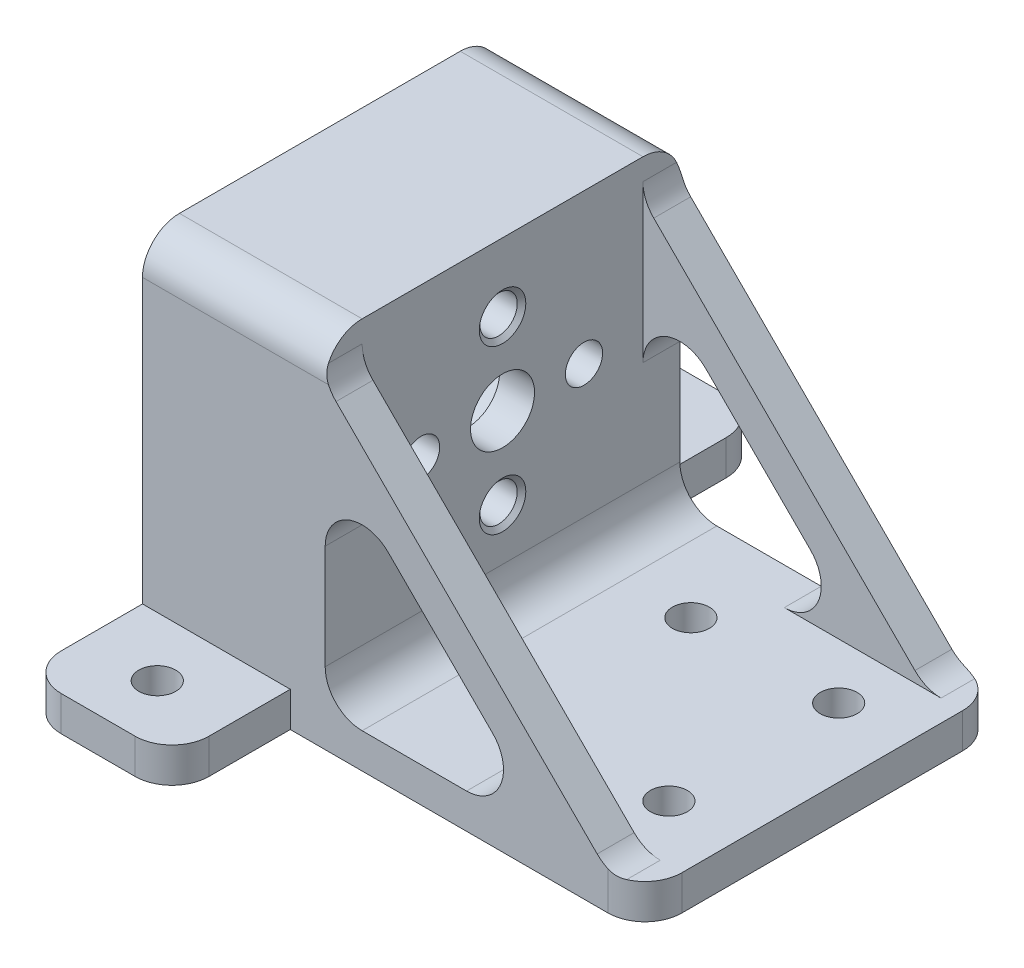
SolidWorks part; units mm, degrees
ref_plane "Front" through (0, 0, 0) normal (0, 0, 1) x (1, 0, 0)
ref_plane "Top" through (0, 0, 0) normal (0, 1, 0) x (1, 0, 0)
ref_plane "Right" through (0, 0, 0) normal (1, 0, 0) x (0, 0, -1)
ref_plane "Plane1" through (0, 0, 0) normal (0, -1, 0) x (1, 0, 0)
sketch "Sketch1" plane through (0, 0, 0) normal (0, -1, 0) x (1, 0, 0)
  line L0 (-15.24, -15.24) -> (15.24, -15.24)
  line L1 (15.24, -15.24) -> (15.24, 15.24)
  line L2 (15.24, 15.24) -> (-15.24, 15.24)
  line L3 (-15.24, 15.24) -> (-15.24, -15.24)
extrude "Boss-Extrude1" add sketch "Sketch1" against normal blind 30.48
sketch "Sketch2" plane through (0, 0, -15.24) normal (0, 0, -1) x (-1, 0, 0)
  line L0 (-15.24, 3) -> (12.24, 3)
  line L1 (12.24, 3) -> (12.24, 30.48)
  line L2 (12.24, 30.48) -> (-15.24, 30.48)
  line L3 (-15.24, 30.48) -> (-15.24, 3)
extrude "Cut-Extrude1" cut sketch "Sketch2" against normal through all
sketch "Sketch4" plane through (0, 3, 0) normal (0, 1, 0) x (-1, 0, 0)
  line L0 (0, 0) -> (-23.6312, 0) construction
  line L1 (12.24, 15.24) -> (12.24, -15.24) construction
  point P3 (-9.35, -7.2958)
  point P4 (-9.35, 7.2958)
  point P5 (3.35, 7.2958)
  point P6 (3.35, -7.2958)
  dimension "D1" = 14.5915
  dimension "D2" = 12.7
  dimension "D3" = 8.89
hole_wizard "#10 Clearance Hole1" positions "Sketch8" profile "Sketch7" hole size "#10" standard "ANSI Inch" end condition through all
sketch "Sketch8" plane through (-12.24, 0, 0) normal (1, 0, 0) x (0, 0, -1)
  line L0 (15.24, 3) -> (15.24, 30.48) construction
  line L1 (-15.24, 30.48) -> (15.24, 30.48) construction
  point P0 (0, 17.605)
  dimension "D1" = 15.24
  dimension "D2" = 12.875
sketch "Sketch7" plane through (-12.24, 17.605, 0) normal (0, 1, 0) x (0, 0, -1)
  line L0 (0, 0) -> (0, 3)
  line L1 (0, 3) -> (2.75, 3)
  line L2 (2.75, 3) -> (2.75, 0)
  line L5 (2.75, 0) -> (0, 0)
  line L11 (0, -6.35) -> (0, 107.95) construction
  dimension "Thru Hole Dia." = 5.5
  dimension "Thru Hole Depth" = 3
hole_wizard "#4 Clearance Hole1" positions "Sketch10" profile "Sketch9" hole size "#4" standard "ANSI Inch"
sketch "Sketch10" plane through (-12.24, 0, 0) normal (1, 0, 0) x (0, 0, -1)
  point P0 (-7, 17.605)
  point P1 (7, 17.605)
  point P2 (0, 24.605)
  point P3 (0, 10.605)
sketch "Sketch9" plane through (-12.24, 17.605, 7) normal (0, 1, 0) x (0, 0, -1)
  line L0 (0, 0) -> (0, 3)
  line L1 (0, 3) -> (1.6, 3)
  line L2 (1.6, 3) -> (1.6, 0)
  line L5 (1.6, 0) -> (0, 0)
  line L11 (0, -6.35) -> (0, 107.95) construction
  dimension "Thru Hole Dia." = 3.2
  dimension "Thru Hole Depth" = 3
chamfer "Chamfer1" distance 0.4 angle 40 2 edges at (-12.24, 10.605, -1.6) (-12.24, 24.605, -1.6)
fillet "Fillet1" radius 3.175 5 edges at (-13.74, 30.48, 15.24) (15.24, 1.5, -15.24) (-13.74, 30.48, -15.24) (15.24, 1.5, 15.24) (-12.24, 3, 0)
sketch "Sketch11" plane through (0, 0, 15.24) normal (0, 0, 1) x (1, 0, 0)
  line L0 (-12.24, 27.305) -> (12.065, 3)
  line L1 (12.065, 3) -> (7.5749, 3)
  line L2 (12.065, 3) -> (-9.065, 3) construction
  line L3 (7.5749, 3) -> (-12.24, 22.8149)
  line L4 (-12.24, 6.175) -> (-12.24, 27.305) construction
  line L5 (-12.24, 22.8149) -> (-12.24, 27.305)
  dimension "D1" = 3.175
extrude "Boss-Extrude2" add sketch "Sketch11" against normal blind 3.175
ref_plane "Plane2" through (0, 0, 0) normal (0, 0, -1) x (-1, 0, 0)
mirror "Mirror1" about plane through (0, 0, 0) normal (0, 0, -1) of "Boss-Extrude2"
sketch "Sketch17" [suppressed] plane through (-15.24, 0, 0) normal (-1, 0, 0) x (0, 0, 1)
  line L0 (15.24, 27.305) -> (15.24, 0) construction
  line L1 (12.065, 30.48) -> (-12.065, 30.48) construction
  point P0 (0, 17.605)
  dimension "D1" = 15.24
  dimension "D2" = 12.875
hole_wizard "Ø10.0mm Dowel Hole1" [suppressed] positions "Sketch18" profile "Sketch19" hole size "Ø10.0" standard "ANSI Metric"
sketch "Sketch18" plane through (-15.24, 0, 0) normal (-1, 0, 0) x (0, 0, 1)
  point P0 (0, 17.605)
sketch "Sketch19" plane through (-15.24, 17.605, 0) normal (0, 1, 0) x (0, 0, 1)
  line L0 (0, 0) -> (0, 6.0523)
  line L1 (0, 6.0523) -> (5, 3.048)
  line L2 (5, 3.048) -> (5, 0)
  line L5 (5, 0) -> (0, 0)
  line L10 (0, 6.0523) -> (-5, 3.048) construction
  line L11 (0, -6.35) -> (0, 107.95) construction
  dimension "Hole Dia." = 10
  dimension "Hole Depth" = 3.048
  dimension "Drill Angle" = 118
sketch "Sketch20" plane through (-15.24, 0, 0) normal (-1, 0, 0) x (0, 0, 1)
  line L4 (15.24, 0) -> (15.24, 27.305)
  line L5 (12.065, 30.48) -> (-12.065, 30.48)
  line L6 (-15.24, 27.305) -> (-15.24, 0)
  line L7 (-15.24, 0) -> (15.24, 0)
  line L8 (15.24, 0) -> (15.24, 27.305)
  line L9 (12.065, 30.48) -> (-12.065, 30.48)
  line L10 (-15.24, 27.305) -> (-15.24, 0)
  line L11 (-15.24, 0) -> (15.24, 0)
  circle A0 centre (0, 17.605) radius 11
  arc A2 (15.24, 27.305) -> (12.065, 30.48) centre (12.065, 27.305) ccw
  arc A3 (-12.065, 30.48) -> (-15.24, 27.305) centre (-12.065, 27.305) ccw
  arc A4 (15.24, 27.305) -> (12.065, 30.48) centre (12.065, 27.305) ccw
  arc A5 (-12.065, 30.48) -> (-15.24, 27.305) centre (-12.065, 27.305) ccw
  dimension "D2" = 22
  dimension "D1" = 0
extrude "Boss-Extrude3" add sketch "Sketch20" along normal blind 12.7
sketch "Sketch21" plane through (0, 0, 0) normal (0, -1, 0) x (1, 0, 0)
  line L0 (-27.94, -15.24) -> (-27.94, 15.24) construction
  line L1 (-27.94, -25.4) -> (-15.24, -25.4)
  line L2 (-27.94, -25.4) -> (-27.94, 25.4)
  line L3 (-27.94, 25.4) -> (-15.24, 25.4)
  line L4 (-15.24, -25.4) -> (-15.24, 25.4)
  line L6 (0, 0) -> (32.0017, 0) construction
  dimension "D1" = 12.7
  dimension "D2" = 50.8
extrude "Boss-Extrude4" add sketch "Sketch21" against normal up to surface (3 mm away) up to face at (7.6854, 3, 0)
fillet "Fillet2" radius 3.175 12 edges at (-12.24, 22.8149, 13.6525) (12.065, 3, 13.6525) (-12.24, 27.305, 13.6525) (-12.24, 27.305, -13.6525) (-12.24, 22.8149, -13.6525) (7.5749, 3, -13.6525) (12.065, 3, -13.6525) (7.5749, 3, 13.6525) (-27.94, 1.5, -25.4) (-15.24, 1.5, -25.4) (-27.94, 1.5, 25.4) (-15.24, 1.5, 25.4)
hole_wizard "1/8 (0.1250) Dowel Hole1" positions "Sketch15" profile "Sketch14" hole size "1/8" standard "ANSI Inch"
sketch "Sketch15" plane through (0, 3, 0) normal (0, 1, 0) x (1, 0, 0)
  line L0 (-21.59, -25.4) -> (-21.59, 25.4) construction
  line L1 (-24.765, -25.4) -> (-18.415, -25.4) construction
  line L2 (-18.415, 25.4) -> (-24.765, 25.4) construction
  line L4 (-15.24, -18.7325) -> (-27.94, -18.7325) construction
  line L5 (-15.24, -22.225) -> (-15.24, -15.24) construction
  line L6 (-27.94, -15.24) -> (-27.94, -22.225) construction
  line L8 (-27.94, 18.7325) -> (-15.24, 18.7325) construction
  line L9 (-27.94, 22.225) -> (-27.94, 15.24) construction
  line L10 (-15.24, 15.24) -> (-15.24, 22.225) construction
  point P0 (-3.35, 7.2958)
  point P3 (9.35, 7.2958)
  point P6 (9.35, -7.2958)
  point P9 (-3.35, -7.2958)
sketch "Sketch14" plane through (-3.35, 3, -7.2958) normal (1, 0, 0) x (0, 0, 1)
  line L0 (0, 0) -> (0, 7.3039)
  line L1 (0, 7.3039) -> (1.5875, 6.35)
  line L2 (1.5875, 6.35) -> (1.5875, 0)
  line L5 (1.5875, 0) -> (0, 0)
  line L10 (0, 7.3039) -> (-1.5875, 6.35) construction
  line L11 (0, -6.35) -> (0, 107.95) construction
  dimension "Hole Dia." = 3.175
  dimension "Hole Depth" = 6.35
  dimension "Drill Angle" = 118
sketch "Sketch22" plane through (0, 3, 0) normal (0, 1, 0) x (1, 0, 0)
  line L0 (-21.59, 25.4) -> (-21.59, -25.4) construction
  line L1 (-18.415, 25.4) -> (-24.765, 25.4) construction
  line L2 (-24.765, -25.4) -> (-18.415, -25.4) construction
  line L3 (-15.24, -15.24) -> (-15.24, -25.4) construction
  line L6 (-15.24, 15.24) -> (-15.24, 25.4) construction
  line L9 (-15.24, -20.32) -> (-27.94, -20.32) construction
  line L10 (-27.94, -15.24) -> (-27.94, -22.225) construction
  line L11 (-15.24, 20.32) -> (-27.94, 20.32) construction
  line L12 (-27.94, 22.225) -> (-27.94, 15.24) construction
  point P14 (0, 0)
  point P18 (-21.59, 20.32)
  point P19 (-21.59, -20.32)
  point P22 (0, 0)
  point P24 (0, 0)
hole_wizard "1/8 (0.1250) Dowel Hole2" positions "Sketch23" profile "Sketch24" hole size "1/8" standard "ANSI Inch"
sketch "Sketch23" plane through (0, 3, 0) normal (0, 1, 0) x (1, 0, 0)
  point P0 (-21.59, 20.32)
  point P3 (-21.59, -20.32)
sketch "Sketch24" plane through (-21.59, 3, -20.32) normal (1, 0, 0) x (0, 0, 1)
  line L0 (0, 0) -> (0, 7.3039)
  line L1 (0, 7.3039) -> (1.5875, 6.35)
  line L2 (1.5875, 6.35) -> (1.5875, 0)
  line L5 (1.5875, 0) -> (0, 0)
  line L10 (0, 7.3039) -> (-1.5875, 6.35) construction
  line L11 (0, -6.35) -> (0, 107.95) construction
  dimension "Hole Dia." = 3.175
  dimension "Hole Depth" = 6.35
  dimension "Drill Angle" = 118
fillet "Fillet3" [suppressed] radius 3.175
